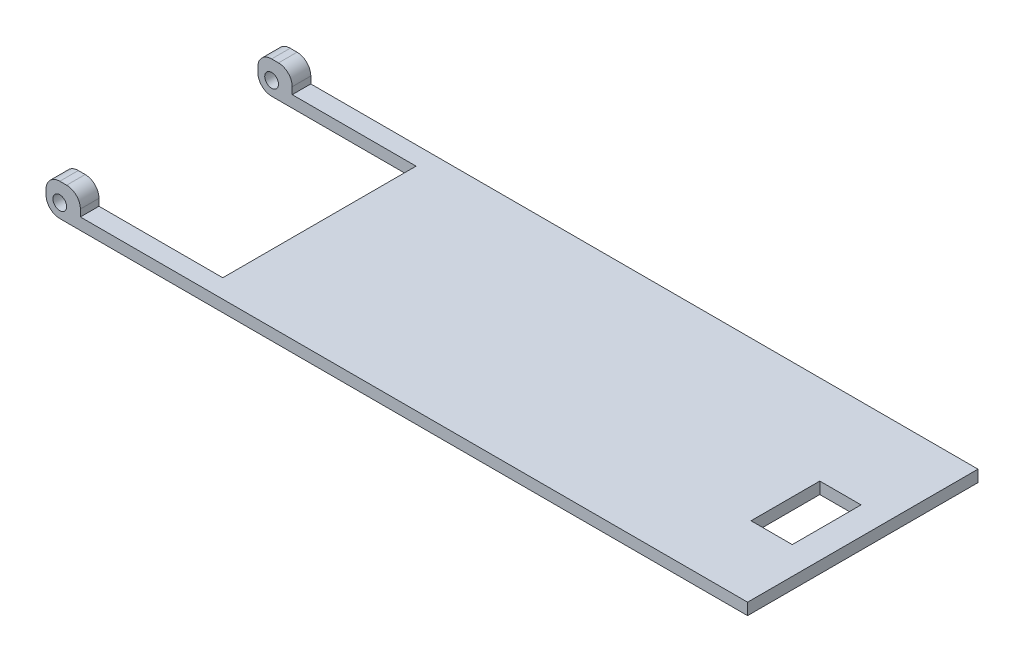
SolidWorks part; units mm, degrees
ref_plane "Front Plane" through (0, 0, 0) normal (0, 0, 1) x (1, 0, 0)
ref_plane "Top Plane" through (0, 0, 0) normal (0, 1, 0) x (1, 0, 0)
ref_plane "Right Plane" through (0, 0, 0) normal (1, 0, 0) x (0, 0, -1)
sketch "Sketch1" plane through (0, 0, 0) normal (0, 1, 0) x (1, 0, 0)
  line L1 (-51, -16.75) -> (51, -16.75)
  line L2 (-51, -16.75) -> (-51, 16.75)
  line L3 (-51, 16.75) -> (51, 16.75)
  line L4 (51, -16.75) -> (51, 16.75)
  line L5 (-51, -16.75) -> (51, 16.75) construction
  line L6 (-51, 16.75) -> (51, -16.75) construction
  point P0 (0, 0)
  dimension "D1" = 102
  dimension "D2" = 33.5
extrude "Boss-Extrude1" add sketch "Sketch1" along normal blind 1.7
sketch "Sketch2" plane through (0, 1.7, 0) normal (0, 1, 0) x (1, 0, 0)
  line L0 (-51, 16.75) -> (-51, -16.75) construction
  line L1 (-51, -14.05) -> (-28, -14.05)
  line L2 (-51, -14.05) -> (-51, 14.05)
  line L3 (-51, 14.05) -> (-28, 14.05)
  line L4 (-28, -14.05) -> (-28, 14.05)
  line L5 (-51, -16.75) -> (51, -16.75) construction
  line L6 (51, 16.75) -> (-51, 16.75) construction
  dimension "D1" = 2.7
  dimension "D2" = 2.7
  dimension "D3" = 23
extrude "Cut-Extrude1" cut sketch "Sketch2" against normal up to vertex (1.7 mm away)
sketch "Sketch4" plane through (0, 1.7, 0) normal (0, 1, 0) x (1, 0, 0)
  line L0 (-51, -16.75) -> (51, -16.75) construction
  line L1 (-51, -14.05) -> (-46, -14.05)
  line L2 (-51, -14.05) -> (-51, -16.75)
  line L3 (-51, -16.75) -> (-46, -16.75)
  line L4 (-46, -14.05) -> (-46, -16.75)
  dimension "D1" = 5
extrude "Boss-Extrude2" add sketch "Sketch4" along normal blind 3
sketch "Sketch5" plane through (0, 0, 16.75) normal (0, 0, 1) x (1, 0, 0)
  line L0 (-51, 0) -> (51, 0) construction
  line L1 (-51, 4.7) -> (-51, 0) construction
  circle A0 centre (-49, 2) radius 1
  dimension "D3" = 2
  dimension "D1" = 2
  dimension "D2" = 2
extrude "Cut-Extrude2" cut sketch "Sketch5" against normal up to vertex (2.7 mm away) contours A0
fillet "Fillet1" radius 2 3 edges at (-51, 0, 15.4) (-51, 4.7, 15.4) (-46, 4.7, 15.4)
ref_plane "Plane1" through (0, 0, 0) normal (0, 0, 1) x (1, 0, 0)
mirror "Mirror2" about plane through (0, 0, 0) normal (0, 0, 1) of "Boss-Extrude2", "Cut-Extrude2", "Fillet1"
sketch "Sketch10" plane through (0, 1.7, 0) normal (0, 1, 0) x (1, 0, 0)
  line L0 (51, -16.75) -> (51, 16.75) construction
  line L1 (41, -6.25) -> (47, -6.25)
  line L2 (41, -6.25) -> (41, 3.75)
  line L3 (41, 3.75) -> (47, 3.75)
  line L4 (47, -6.25) -> (47, 3.75)
  line L5 (41, -6.25) -> (47, 3.75) construction
  line L6 (41, 3.75) -> (47, -6.25) construction
  line L8 (-46, -16.75) -> (51, -16.75) construction
  point P0 (44, -1.25)
  dimension "D1" = 4
  dimension "D2" = 6
  dimension "D3" = 10.5
  dimension "D4" = 10
extrude "Cut-Extrude3" cut sketch "Sketch10" against normal up to vertex (1.7 mm away) up to point (51, 0, -16.75)
